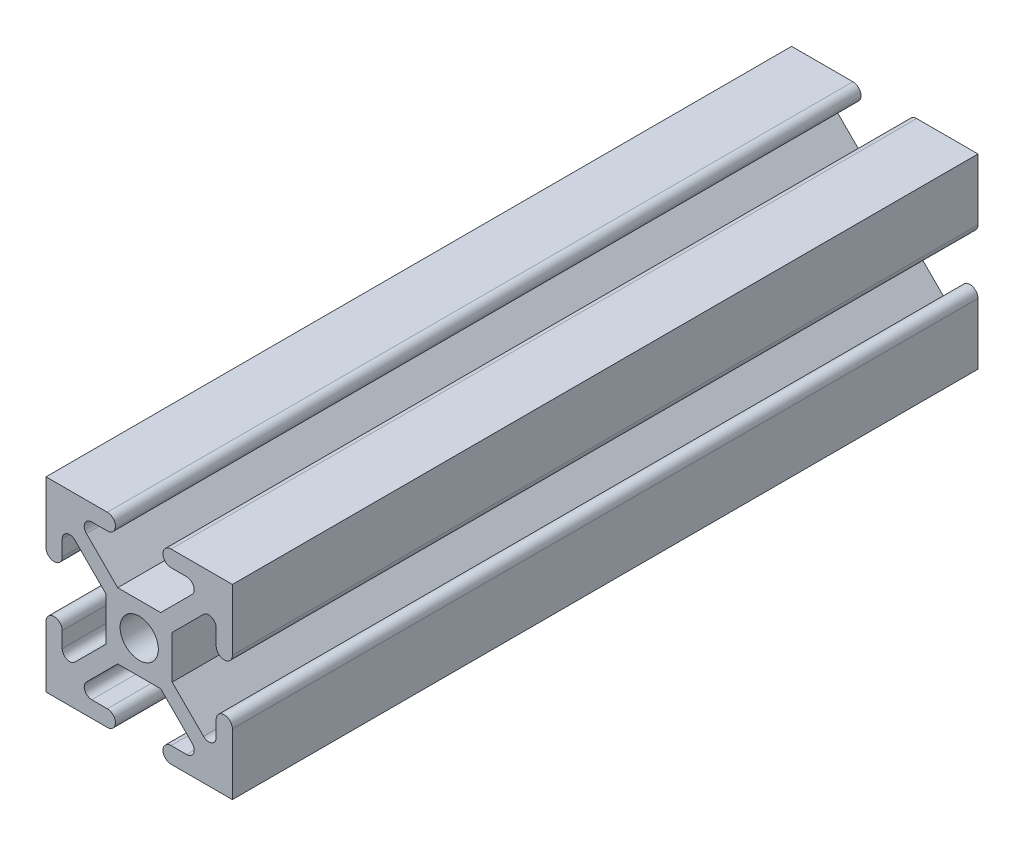
SolidWorks part; units mm, degrees
ref_plane "Front Plane" through (0, 0, 0) normal (0, 0, 1) x (1, 0, 0)
ref_plane "Top Plane" through (0, 0, 0) normal (0, 1, 0) x (1, 0, 0)
ref_plane "Right Plane" through (0, 0, 0) normal (1, 0, 0) x (0, 0, -1)
sketch "Sketch1" plane through (0, 0, 0) normal (0, 0, 1) x (1, 0, 0)
  line L2 (-12.7, -12.7) -> (-4.3434, -12.7)
  line L3 (-4.3434, -10.4902) -> (-6.4748, -10.4902)
  line L4 (-7.1932, -8.7558) -> (-2.9332, -4.4958)
  line L5 (-2.9332, -4.4958) -> (2.9332, -4.4958)
  line L6 (2.9332, -4.4958) -> (7.1932, -8.7558)
  line L7 (6.4748, -10.4902) -> (4.3434, -10.4902)
  line L8 (4.3434, -12.7) -> (12.7, -12.7)
  line L11 (12.7, -12.7) -> (12.7, -4.3434)
  line L12 (10.4902, -4.3434) -> (10.4902, -6.4748)
  line L13 (8.7558, -7.1932) -> (4.4958, -2.9332)
  line L14 (4.4958, -2.9332) -> (4.4958, 2.9332)
  line L15 (4.4958, 2.9332) -> (8.7558, 7.1932)
  line L16 (10.4902, 6.4748) -> (10.4902, 4.3434)
  line L17 (12.7, 4.3434) -> (12.7, 12.7)
  line L20 (12.7, 12.7) -> (4.3434, 12.7)
  line L21 (4.3434, 10.4902) -> (6.4748, 10.4902)
  line L22 (7.1932, 8.7558) -> (2.9332, 4.4958)
  line L23 (2.9332, 4.4958) -> (-2.9332, 4.4958)
  line L24 (-2.9332, 4.4958) -> (-7.1932, 8.7558)
  line L25 (-6.4748, 10.4902) -> (-4.3434, 10.4902)
  line L26 (-4.3434, 12.7) -> (-12.7, 12.7)
  line L29 (-12.7, 12.7) -> (-12.7, 4.3434)
  line L30 (-10.4902, 4.3434) -> (-10.4902, 6.4748)
  line L31 (-8.7558, 7.1932) -> (-4.4958, 2.9332)
  line L32 (-4.4958, 2.9332) -> (-4.4958, -2.9332)
  line L33 (-4.4958, -2.9332) -> (-8.7558, -7.1932)
  line L34 (-10.4902, -6.4748) -> (-10.4902, -4.3434)
  line L35 (-12.7, -4.3434) -> (-12.7, -12.7)
  circle A0 centre (0, 0) radius 2.6035
  arc A6 (-4.3434, -12.7) -> (-4.3434, -10.4902) centre (-4.3434, -11.5951) ccw
  arc A7 (-6.4748, -10.4902) -> (-7.1932, -8.7558) centre (-6.4748, -9.4742) cw
  arc A10 (7.1932, -8.7558) -> (6.4748, -10.4902) centre (6.4748, -9.4742) cw
  arc A11 (4.3434, -10.4902) -> (4.3434, -12.7) centre (4.3434, -11.5951) ccw
  arc A17 (12.7, -4.3434) -> (10.4902, -4.3434) centre (11.5951, -4.3434) ccw
  arc A18 (10.4902, -6.4748) -> (8.7558, -7.1932) centre (9.4742, -6.4748) cw
  arc A21 (8.7558, 7.1932) -> (10.4902, 6.4748) centre (9.4742, 6.4748) cw
  arc A22 (10.4902, 4.3434) -> (12.7, 4.3434) centre (11.5951, 4.3434) ccw
  arc A28 (4.3434, 12.7) -> (4.3434, 10.4902) centre (4.3434, 11.5951) ccw
  arc A29 (6.4748, 10.4902) -> (7.1932, 8.7558) centre (6.4748, 9.4742) cw
  arc A32 (-7.1932, 8.7558) -> (-6.4748, 10.4902) centre (-6.4748, 9.4742) cw
  arc A33 (-4.3434, 10.4902) -> (-4.3434, 12.7) centre (-4.3434, 11.5951) ccw
  arc A39 (-12.7, 4.3434) -> (-10.4902, 4.3434) centre (-11.5951, 4.3434) ccw
  arc A40 (-10.4902, 6.4748) -> (-8.7558, 7.1932) centre (-9.4742, 6.4748) cw
  arc A43 (-8.7558, -7.1932) -> (-10.4902, -6.4748) centre (-9.4742, -6.4748) cw
  arc A44 (-10.4902, -4.3434) -> (-12.7, -4.3434) centre (-11.5951, -4.3434) ccw
  point P101 (-4.4958, 0)
  point P102 (0, 4.4958)
  point P103 (4.4958, 0)
  point P127 (0, -4.4958)
extrude "Boss-Extrude1" add sketch "Sketch1" against normal blind 101.6
